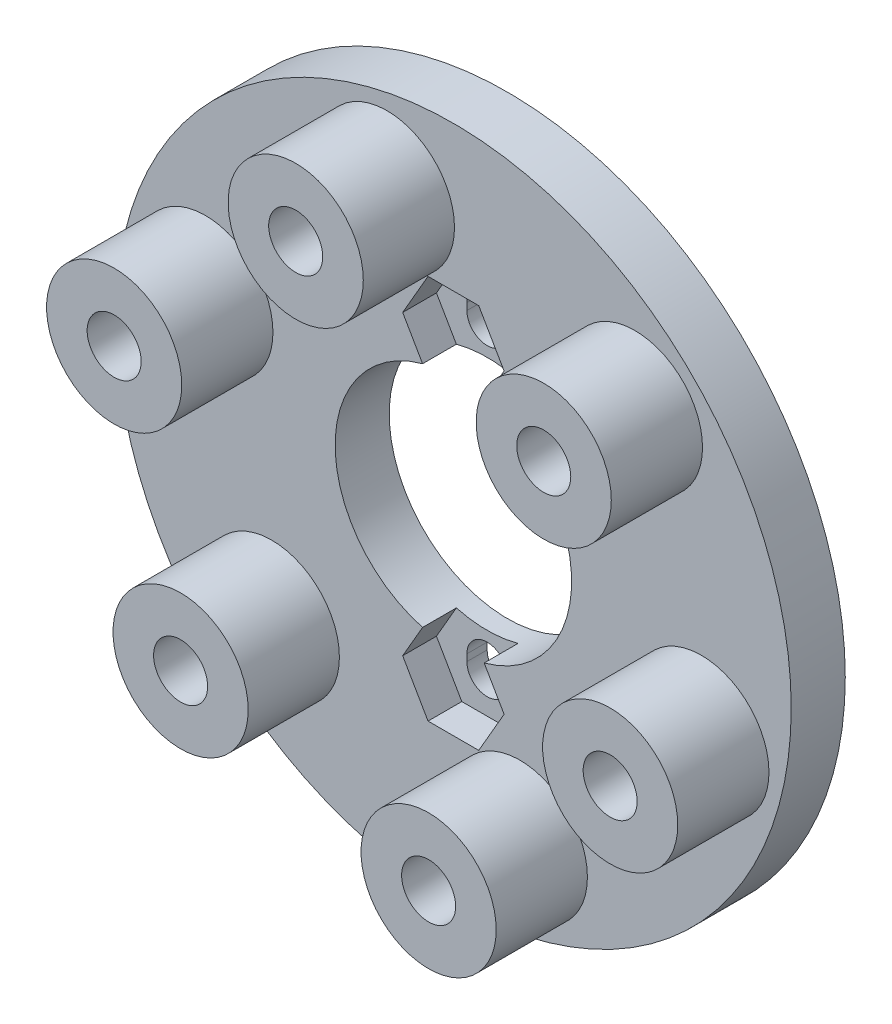
SolidWorks part; units mm, degrees
ref_plane "Front Plane" through (0, 0, 0) normal (0, 0, 1) x (1, 0, 0)
ref_plane "Top Plane" through (0, 0, 0) normal (0, 1, 0) x (1, 0, 0)
ref_plane "Right Plane" through (0, 0, 0) normal (1, 0, 0) x (0, 0, -1)
sketch "Sketch1" plane through (0, 0, 0) normal (0, 0, 1) x (1, 0, 0)
  line L1 (-1.5, 11) -> (-1.5, 11.5)
  line L2 (1.5, 11) -> (1.5, 11.5)
  line L3 (-1.5, -11) -> (-1.5, -11.5)
  line L4 (1.5, -11) -> (1.5, -11.5)
  arc A2 (-1.5, 11) -> (1.5, 11) centre (0, 11) ccw
  arc A3 (1.5, -11) -> (-1.5, -11) centre (0, -11) ccw
  circle A8 centre (0, 0) radius 25
  circle A9 centre (0, 0) radius 8.75
  arc A10 (1.5, 11.5) -> (-1.5, 11.5) centre (0, 11.5) ccw
  arc A11 (-1.5, -11.5) -> (1.5, -11.5) centre (0, -11.5) ccw
  dimension "D1" = 50
  dimension "D2" = 17.5
  dimension "D3" = 3
  dimension "D4" = 3
  dimension "D5" = 0.5
  dimension "D6" = 3
  dimension "D7" = 0.5
  dimension "D8" = 11
  dimension "D10" = 3
  dimension "D9" = 11
extrude "Boss-Extrude1" add sketch "Sketch1" along normal blind 4
sketch "Sketch2" plane through (0, 0, 4) normal (0, 0, 1) x (1, 0, 0)
  circle A1 centre (-4.9176, 18.3526) radius 5
  circle A2 centre (-18.3526, 4.9176) radius 5
  circle A3 centre (-13.435, -13.435) radius 5
  circle A4 centre (4.9176, -18.3526) radius 5
  circle A5 centre (18.3526, -4.9176) radius 5
  circle A6 centre (13.435, 13.435) radius 5
  circle A7 centre (-4.9176, 18.3526) radius 2
  circle A8 centre (-18.3526, 4.9176) radius 2
  circle A9 centre (-13.435, -13.435) radius 2
  circle A10 centre (4.9176, -18.3526) radius 2
  circle A11 centre (18.3526, -4.9176) radius 2
  circle A12 centre (13.435, 13.435) radius 2
  circle A13 centre (0, 0) radius 8.75 construction
  dimension "D2" = 10
  dimension "D3" = 10
  dimension "D4" = 10
  dimension "D5" = 10
  dimension "D6" = 10
  dimension "D7" = 10
  dimension "D8" = 4
  dimension "D9" = 4
  dimension "D10" = 4
  dimension "D11" = 4
  dimension "D12" = 4
  dimension "D13" = 4
  dimension "D14" = 19
  dimension "D15" = 19
  dimension "D16" = 19
  dimension "D17" = 19
  dimension "D18" = 19
  dimension "D19" = 19
extrude "Boss-Extrude2" add sketch "Sketch2" along normal blind 6.75
sketch "Sketch5" plane through (0, 0, 4) normal (0, 0, 1) x (1, 0, 0)
  circle A0 centre (-18.3526, 4.9176) radius 2
  circle A1 centre (-13.435, -13.435) radius 2
  circle A2 centre (4.9176, -18.3526) radius 2
  circle A3 centre (18.3526, -4.9176) radius 2
  circle A4 centre (13.435, 13.435) radius 2
  circle A5 centre (-4.9176, 18.3526) radius 2
extrude "Cut-Extrude1" cut sketch "Sketch5" against normal blind 6.75
sketch "Sketch6" plane through (0, 0, 4) normal (0, 0, 1) x (1, 0, 0)
  line L0 (30.9017, 0) -> (-30.2275, 0) construction
  line L5 (1.8764, -7.75) -> (-1.8764, -7.75)
  line L7 (1.8764, 14.25) -> (3.7528, 11)
  line L10 (-1.8764, 14.25) -> (1.8764, 14.25)
  line L11 (-3.7528, 11) -> (-1.8764, 14.25)
  line L12 (-1.8764, 7.75) -> (-3.7528, 11)
  line L13 (-1.8764, -7.75) -> (-3.7528, -11)
  line L14 (-3.7528, -11) -> (-1.8764, -14.25)
  line L15 (-1.8764, -14.25) -> (1.8764, -14.25)
  line L16 (1.8764, -14.25) -> (3.7528, -11)
  line L17 (3.7528, -11) -> (1.8764, -7.75)
  line L18 (1.8764, 7.75) -> (-1.8764, 7.75)
  line L19 (3.7528, 11) -> (1.8764, 7.75)
  circle A3 centre (0, -11) radius 1.5 construction
  point P0 (0, -7.75)
  point P1 (0, -14.25)
  point P3 (-2.8146, -9.375)
  point P4 (2.8146, -12.625)
  point P5 (2.8146, -9.375)
  point P6 (-2.8146, -12.625)
  dimension "D1" = 6.5
  dimension "D2" = 6.5
  dimension "D3" = 6.5
  dimension "D4" = 3.25
  dimension "D5" = 3.25
  dimension "D6" = 3.25
  dimension "D7" = 3.25
  dimension "D8" = 3.25
  dimension "D9" = 3.25
extrude "Cut-Extrude2" cut sketch "Sketch6" against normal blind 2.5
